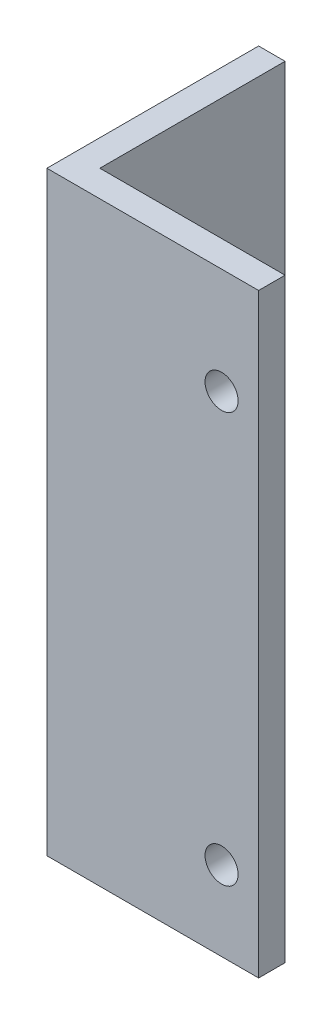
SolidWorks part; units mm, degrees
ref_plane "Front Plane" through (0, 0, 0) normal (0, 0, 1) x (1, 0, 0)
ref_plane "Top Plane" through (0, 0, 0) normal (0, 1, 0) x (1, 0, 0)
ref_plane "Right Plane" through (0, 0, 0) normal (1, 0, 0) x (0, 0, -1)
sketch "Sketch1" plane through (0, 0, 0) normal (0, 1, 0) x (1, 0, 0)
  line L0 (0, 0) -> (16, 0)
  line L1 (16, 0) -> (16, 2)
  line L2 (16, 2) -> (2, 2)
  line L3 (2, 2) -> (2, 16)
  line L4 (2, 16) -> (0, 16)
  line L5 (0, 16) -> (0, 0)
  dimension "D1" = 16
  dimension "D2" = 16
  dimension "D3" = 2
  dimension "D4" = 2
extrude "Boss-Extrude1" add sketch "Sketch1" along normal blind 45
sketch "Sketch2" plane through (0, 0, -2) normal (0, 0, -1) x (-1, 0, 0)
  line L0 (0, 45) -> (0, 0) construction
  line L1 (-16, 45) -> (-2, 45) construction
  circle A0 centre (-13.2, 37) radius 1.25
  circle A1 centre (-13.2, 6) radius 1.25
  point P6 (0, 0)
  point P7 (-13.2, 51.194)
  dimension "D3" = 2.5
  dimension "D4" = 2.5
  dimension "D1" = 13.2
  dimension "D2" = 31
  dimension "D5" = 8
extrude "Cut-Extrude1" cut sketch "Sketch2" against normal through all
sketch "Sketch3" plane through (2, 0, 0) normal (1, 0, 0) x (0, 0, -1)
  line L0 (2, 0) -> (16, 0) construction
  line L1 (16, 45) -> (16, 0) construction
  circle A0 centre (13, 9.5) radius 1.25
  circle A1 centre (5, 13.5) radius 1.25
  point P6 (0, 0)
  point P8 (16, 6.8155)
  dimension "D2" = 2.5
  dimension "D3" = 2.5
  dimension "D1" = 4
  dimension "D4" = 9.5
  dimension "D5" = 8
  dimension "D6" = 3
extrude "Cut-Extrude2" cut sketch "Sketch3" against normal through all
